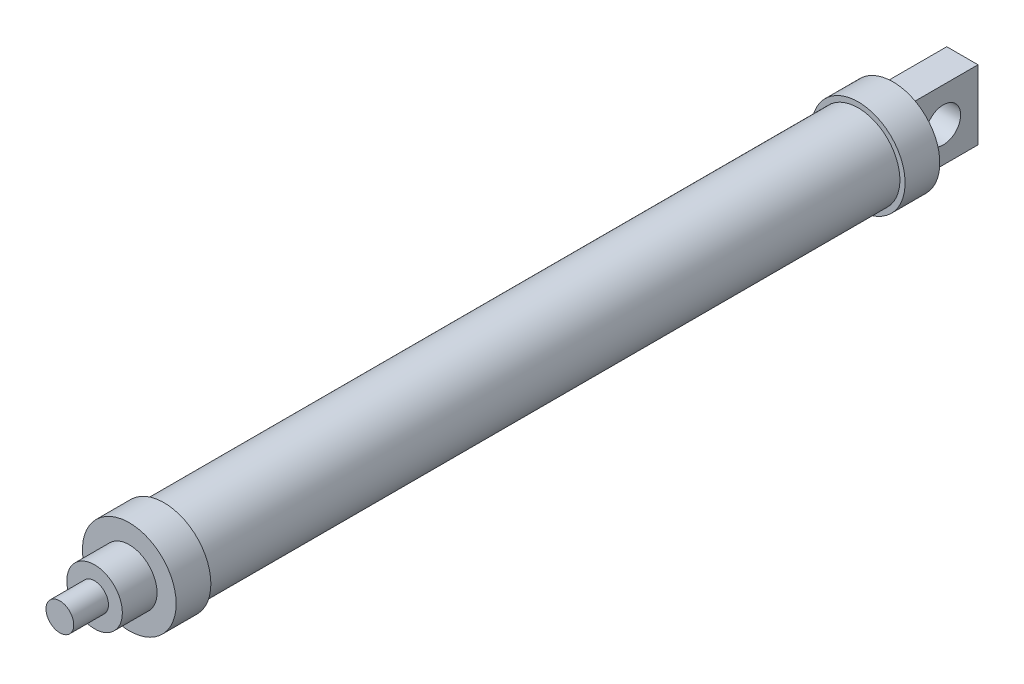
SolidWorks part; units mm, degrees
ref_plane "Front Plane" through (0, 0, 0) normal (0, 0, 1) x (1, 0, 0)
ref_plane "Top Plane" through (0, 0, 0) normal (0, 1, 0) x (1, 0, 0)
ref_plane "Right Plane" through (0, 0, 0) normal (1, 0, 0) x (0, 0, -1)
sketch "Sketch1" plane through (0, 0, 0) normal (0, 0, 1) x (1, 0, 0)
  circle A0 centre (0, 0) radius 13.5
  dimension "D1" = 27
extrude "Boss-Extrude1" add sketch "Sketch1" along normal blind 10
sketch "Sketch2" plane through (0, 0, 10) normal (0, 0, 1) x (1, 0, 0)
  circle A0 centre (0, 0) radius 8
  dimension "D1" = 16
extrude "Boss-Extrude2" add sketch "Sketch2" along normal blind 10
sketch "Sketch3" plane through (0, 0, 0) normal (0, 0, -1) x (-1, 0, 0)
  circle A0 centre (0, 0) radius 12
  dimension "D1" = 24
extrude "Boss-Extrude3" add sketch "Sketch3" along normal blind 200
sketch "Sketch4" plane through (0, 0, -200) normal (0, 0, -1) x (-1, 0, 0)
  circle A0 centre (0, 0) radius 13.5
  dimension "D1" = 27
extrude "Boss-Extrude4" add sketch "Sketch4" along normal blind 10 contours A0
sketch "Sketch5" plane through (0, 0, -210) normal (0, 0, -1) x (-1, 0, 0)
  line L1 (4.5, -10) -> (-4.5, -10)
  line L2 (4.5, -10) -> (4.5, 10)
  line L3 (4.5, 10) -> (-4.5, 10)
  line L4 (-4.5, -10) -> (-4.5, 10)
  line L5 (4.5, -10) -> (-4.5, 10) construction
  line L6 (4.5, 10) -> (-4.5, -10) construction
  point P0 (0, 0)
  dimension "D1" = 9
  dimension "D2" = 20
extrude "Boss-Extrude5" add sketch "Sketch5" along normal blind 20
sketch "Sketch6" plane through (4.5, 0, 0) normal (1, 0, 0) x (0, 0, -1)
  line L0 (210, 10) -> (230, -10) construction
  line L1 (230, -10) -> (210, -10) construction
  line L2 (230, -10) -> (230, 10) construction
  line L3 (230, 10) -> (210, -10) construction
  circle A0 centre (220, 0) radius 5
  dimension "D1" = 10
extrude "Cut-Extrude1" cut sketch "Sketch6" against normal blind 20 contours A0
sketch "Sketch8" plane through (0, 0, 20) normal (0, 0, 1) x (1, 0, 0)
  circle A0 centre (0, 0) radius 4
  dimension "D1" = 8
extrude "Boss-Extrude6" add sketch "Sketch8" along normal blind 10
